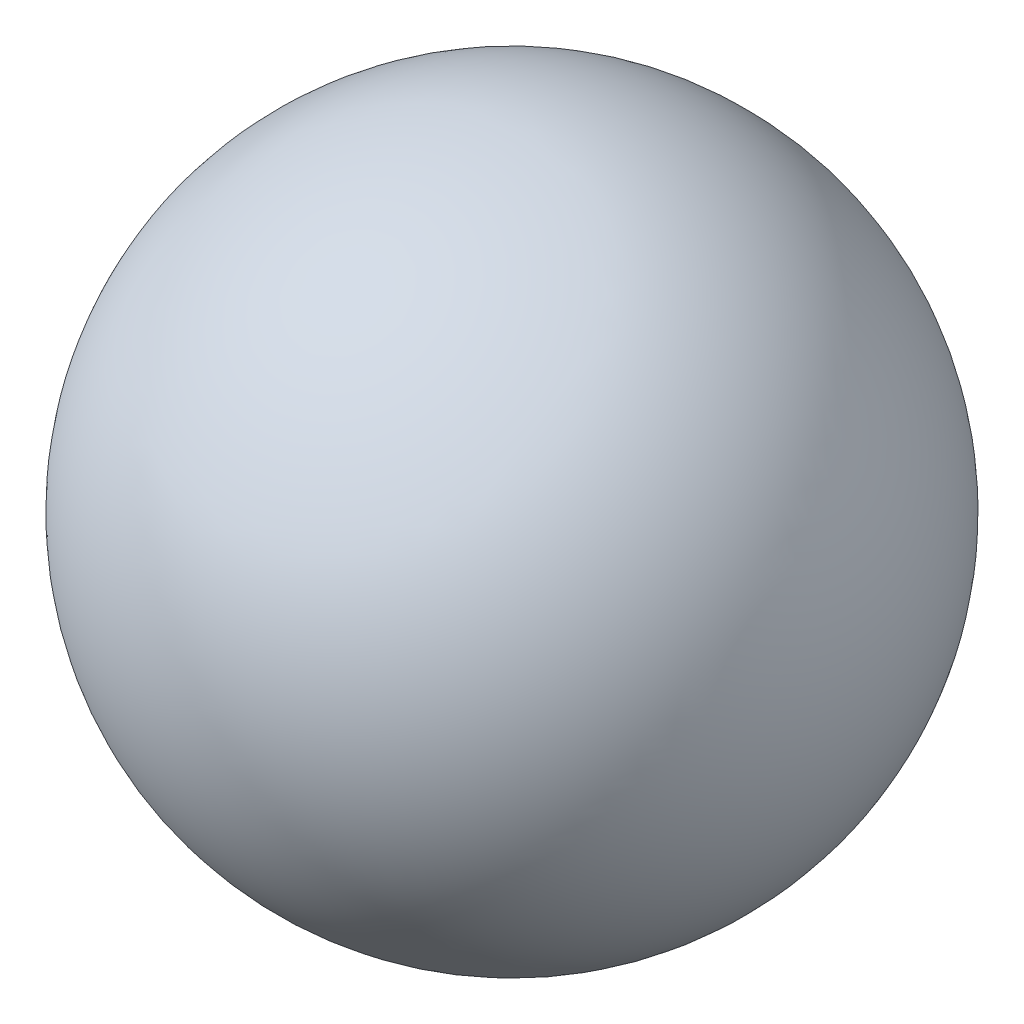
SolidWorks part; units mm, degrees
ref_plane "Front Plane" through (0, 0, 0) normal (0, 0, 1) x (1, 0, 0)
ref_plane "Top Plane" through (0, 0, 0) normal (0, 1, 0) x (1, 0, 0)
ref_plane "Right Plane" through (0, 0, 0) normal (1, 0, 0) x (0, 0, -1)
sketch "Sketch2" plane through (0, 0, 0) normal (0, 0, 1) x (1, 0, 0)
  line L0 (-45, 0) -> (45, 0)
  arc A0 (-45, 0) -> (45, 0) centre (0, 0) ccw
  dimension "D1" = 90
revolve "Revolve1" add sketch "Sketch2" angle 360 about L0
scale "Scale1" scale about centroid uniform scaling yes scale factor 0.277778
